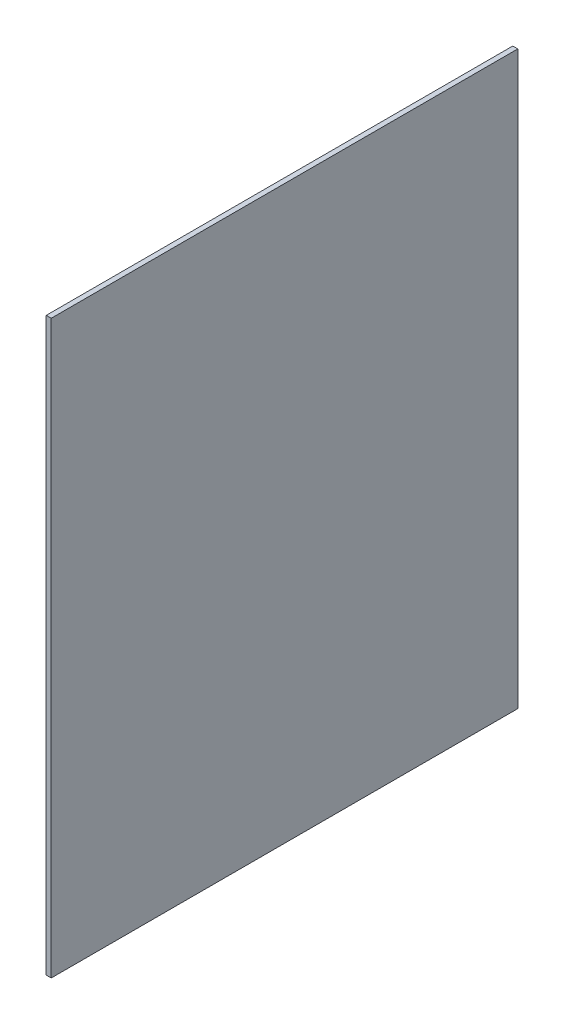
SolidWorks part; units mm, degrees
material "Glass"
ref_plane "Front Plane" through (0, 0, 0) normal (0, 0, 1) x (1, 0, 0)
ref_plane "Top Plane" through (0, 0, 0) normal (0, 1, 0) x (1, 0, 0)
ref_plane "Right Plane" through (0, 0, 0) normal (1, 0, 0) x (0, 0, -1)
sketch "Sketch1" plane through (0, 0, 0) normal (1, 0, 0) x (0, 0, -1)
  line L1 (-36.9162, 1036.1976) -> (849.6932, 1036.1976)
  line L2 (-36.9162, 1036.1976) -> (-36.9162, -49.6524)
  line L3 (-36.9162, -49.6524) -> (849.6932, -49.6524)
  line L4 (849.6932, 1036.1976) -> (849.6932, -49.6524)
  dimension "D1" = 1085.85
extrude "Boss-Extrude1" add sketch "Sketch1" along normal blind 9.525 contours L2 L1 L4 L3
